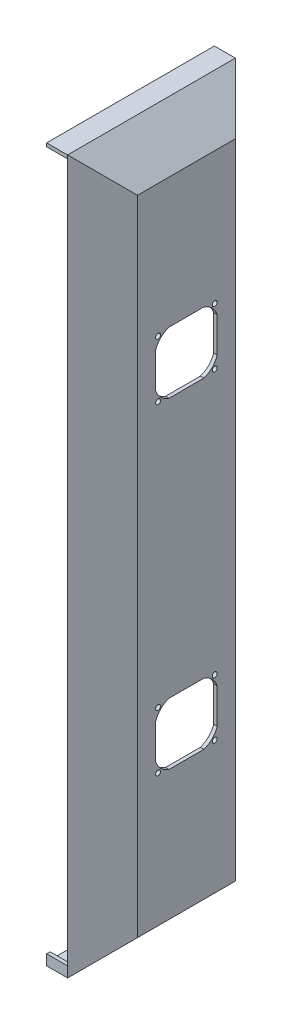
SolidWorks part; units mm, degrees
material "Custom Plastic"
ref_plane "X-Y Datum" through (0, 0, 0) normal (0, 0, 1) x (1, 0, 0)
ref_plane "X-Z Datum" through (0, 0, 0) normal (0, 1, 0) x (1, 0, 0)
ref_plane "Y-Z Datum" through (0, 0, 0) normal (1, 0, 0) x (0, 0, -1)
sketch "Sketch2" plane through (0, 0, 0) normal (1, 0, 0) x (0, 0, -1)
  line L1 (-76.2, -323.85) -> (76.2, -323.85)
  line L2 (-76.2, -323.85) -> (-76.2, 323.85)
  line L3 (-76.2, 323.85) -> (76.2, 323.85)
  line L4 (76.2, -323.85) -> (76.2, 323.85)
  line L5 (-76.2, -323.85) -> (76.2, 323.85) construction
  line L6 (-76.2, 323.85) -> (76.2, -323.85) construction
  point P0 (0, 0)
  dimension "D1" = 647.7
  dimension "D2" = 152.4
extrude "Boss-Extrude1" add sketch "Sketch2" along normal blind 50.8
chamfer "Chamfer1" distance 31.75 angle 45 2 edges at (50.8, 0, -76.2) (50.8, 0, 76.2)
chamfer "Chamfer2" distance 31.75 angle 45 2 edges at (50.8, -323.85, 0) (50.8, 323.85, 0)
shell "Shell1" thickness 3.175
sketch "Sketch3" plane through (0, 0, 0) normal (-1, 0, 0) x (0, 0, 1)
  line L0 (-76.2, -323.85) -> (-76.2, 323.85) construction
  line L1 (-73.025, 320.675) -> (-76.2, 320.675)
  line L2 (-73.025, 320.675) -> (-73.025, -314.4534)
  line L3 (-73.025, -314.4534) -> (-76.2, -314.4534)
  line L4 (-76.2, 320.675) -> (-76.2, -314.4534)
  line L5 (76.2, 323.85) -> (76.2, -323.85) construction
  line L6 (73.025, 320.675) -> (76.2, 320.675)
  line L7 (73.025, 320.675) -> (73.025, -314.325)
  line L8 (73.025, -314.325) -> (76.2, -314.325)
  line L9 (76.2, 320.675) -> (76.2, -314.325)
extrude "Cut-Extrude1" cut sketch "Sketch3" against normal blind 19.05
sketch "Sketch4" plane through (50.8, 0, 0) normal (1, 0, 0) x (0, 0, -1)
  line L0 (-44.45, 0) -> (44.45, 0) construction
  line L1 (-44.45, 292.1) -> (-44.45, -292.1) construction
  line L2 (44.45, -292.1) -> (44.45, 292.1) construction
  line L3 (0, 27.94) -> (0, -27.94) construction
  line L4 (-29.25, 175.3) -> (29.25, 175.3) construction
  line L5 (-29.25, 175.3) -> (-29.25, 116.8) construction
  line L6 (-29.25, 116.8) -> (29.25, 116.8) construction
  line L7 (29.25, 175.3) -> (29.25, 116.8) construction
  line L8 (-29.25, 175.3) -> (29.25, 116.8) construction
  line L9 (-29.25, 116.8) -> (29.25, 175.3) construction
  line L10 (0, 0) -> (0, 292.1) construction
  line L11 (44.45, 292.1) -> (-44.45, 292.1) construction
  line L12 (-27.98, 161.925) -> (-27.98, 130.175)
  line L13 (-25.75, 171.8) -> (25.75, 171.8) construction
  line L14 (-25.75, 171.8) -> (-25.75, 120.3) construction
  line L15 (-25.75, 120.3) -> (25.75, 120.3) construction
  line L16 (25.75, 171.8) -> (25.75, 120.3) construction
  line L17 (-25.75, 171.8) -> (25.75, 120.3) construction
  line L18 (-25.75, 120.3) -> (25.75, 171.8) construction
  line L19 (-15.875, 174.03) -> (15.875, 174.03)
  line L20 (27.98, 161.925) -> (27.98, 130.175)
  line L21 (-15.875, 118.07) -> (15.875, 118.07)
  line L22 (-27.98, -161.925) -> (-27.98, -130.175)
  line L23 (-15.875, -118.07) -> (15.875, -118.07)
  line L24 (27.98, -161.925) -> (27.98, -130.175)
  line L25 (-15.875, -174.03) -> (15.875, -174.03)
  circle A0 centre (-25.75, 171.8) radius 2.25
  circle A1 centre (25.75, 171.8) radius 2.25
  circle A2 centre (-25.75, 120.3) radius 2.25
  circle A3 centre (25.75, 120.3) radius 2.25
  arc A4 (-27.98, 130.175) -> (-15.875, 118.07) centre (-9.8934, 136.1566) ccw
  arc A5 (-27.98, 161.925) -> (-15.875, 174.03) centre (-9.8934, 155.9434) cw
  arc A6 (15.875, 174.03) -> (27.98, 161.925) centre (9.8934, 155.9434) cw
  arc A7 (15.875, 118.07) -> (27.98, 130.175) centre (9.8934, 136.1566) ccw
  circle A8 centre (-25.75, -120.3) radius 2.25
  arc A9 (-27.98, -130.175) -> (-15.875, -118.07) centre (-9.8934, -136.1566) cw
  circle A10 centre (25.75, -120.3) radius 2.25
  arc A11 (15.875, -118.07) -> (27.98, -130.175) centre (9.8934, -136.1566) cw
  circle A12 centre (25.75, -171.8) radius 2.25
  arc A13 (15.875, -174.03) -> (27.98, -161.925) centre (9.8934, -155.9434) ccw
  arc A14 (-27.98, -161.925) -> (-15.875, -174.03) centre (-9.8934, -155.9434) ccw
  circle A15 centre (-25.75, -171.8) radius 2.25
  point P6 (0, 146.05)
  point P18 (0, 146.05)
  point P19 (0, 146.05)
  point P30 (-27.98, 146.05)
  point P31 (-25.75, 146.05)
  point P34 (0, 174.03)
  point P37 (27.98, 146.05)
  point P38 (25.75, 146.05)
  point P41 (0, 118.07)
  dimension "D4" = 31.75
  dimension "D1" = 58.5
  dimension "D2" = 58.5
  dimension "D3" = 51.5
  dimension "D5" = 1.27
  dimension "D6" = 31.75
  dimension "D7" = 1.27
  dimension "D8" = 31.75
  dimension "D9" = 1.27
  dimension "D10" = 31.75
  dimension "D11" = 1.27
extrude "Cut-Extrude2" cut sketch "Sketch4" against normal through all both and the other way through all
